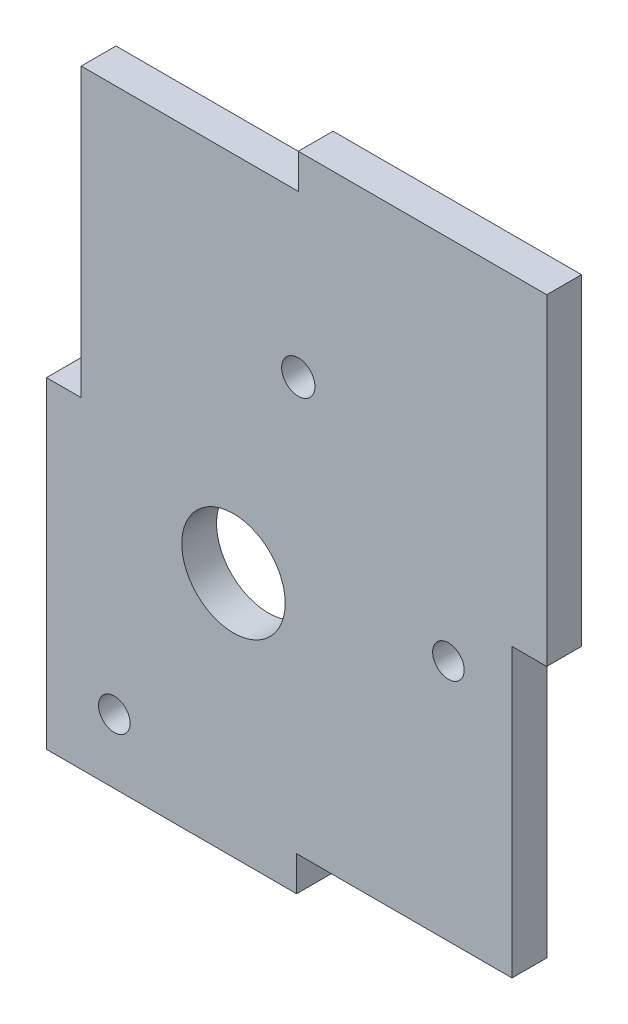
SolidWorks part; units mm, degrees
ref_plane "Front Plane" through (0, 0, 0) normal (0, 0, 1) x (1, 0, 0)
ref_plane "Top Plane" through (0, 0, 0) normal (0, 1, 0) x (1, 0, 0)
ref_plane "Right Plane" through (0, 0, 0) normal (1, 0, 0) x (0, 0, -1)
sketch "backSketch" plane through (0, 0, 0) normal (0, 0, 1) x (1, 0, 0)
  line L1 (0, 0) -> (38.1, 0)
  line L2 (0, 0) -> (0, 50.8)
  line L3 (0, 50.8) -> (38.1, 50.8)
  line L4 (38.1, 0) -> (38.1, 50.8)
  line L5 (2.9253, 2.6131) -> (32.4753, 21.4662) construction
  line L6 (13.4652, 18.6777) -> (19.1967, 36.5785) construction
  line L7 (13.4652, 18.6777) -> (17.7003, 12.0397) construction
  line L9 (19.1967, 50.8) -> (19.1967, 53.8734)
  line L10 (19.1967, 36.5785) -> (19.1967, 50.8) construction
  line L12 (19.1967, 53.8734) -> (41.1734, 53.8734)
  line L13 (41.1734, 53.8734) -> (41.1734, 25.4)
  line L14 (41.1734, 25.4) -> (38.1, 25.4)
  line L15 (0, 25.4) -> (-3.0734, 25.4)
  line L16 (-3.0734, 25.4) -> (-3.0734, -3.0734)
  line L17 (-3.0734, -3.0734) -> (19.05, -3.0734)
  line L18 (19.05, -3.0734) -> (19.05, 0)
  circle A0 centre (2.9253, 2.6131) radius 1.397
  circle A1 centre (32.4753, 21.4662) radius 1.397
  circle A3 centre (13.4652, 18.6777) radius 4.572
  circle A4 centre (19.1967, 36.5785) radius 1.4732
  point P10 (17.7003, 12.0397)
  dimension "D2" = 3.0734
  dimension "D3" = 3.0734
  dimension "holeDia" = 2.794
  dimension "D4" = 3.0734
  dimension "motorAxleDia" = 9.144
  dimension "D1" = 3.0734
  dimension "nailAxleDia" = 2.9464
  dimension "width" = 38.1
  dimension "height" = 50.8
  dimension "MtoA" = 7.874
  dimension "hole2hole" = 35.052
  dimension "x1" = 5.6247
extrude "Boss-Extrude1" add sketch "backSketch" along normal blind 3.0734 contours L14 L13 L12 L9 L3 L4 | L17 L18 L1 L2 L15 L16 | L1 L4 L3 L2 A4 A3 A1 A0
